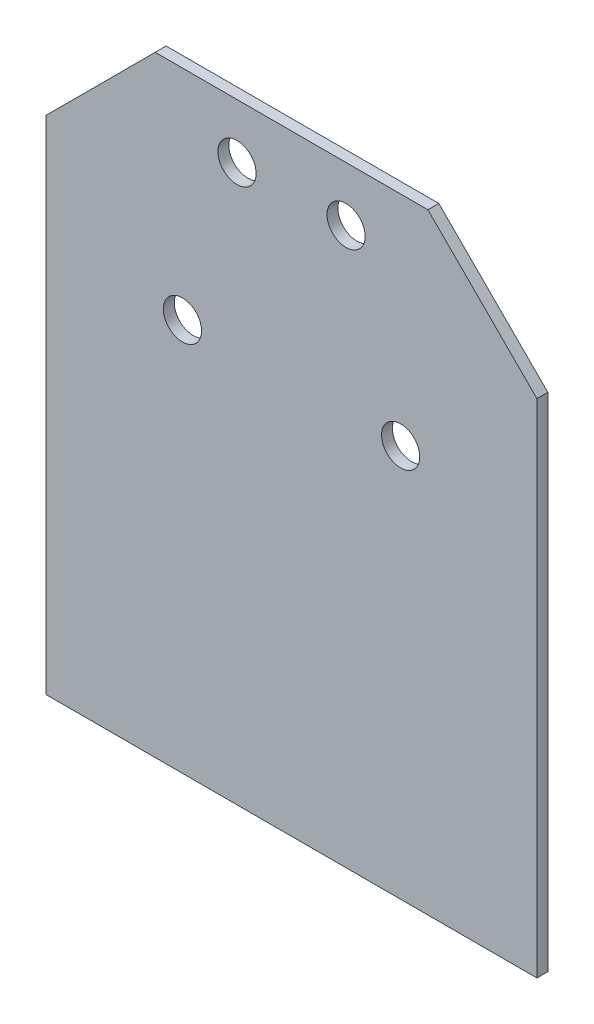
SolidWorks part; units mm, degrees
ref_plane "Piano frontale" through (0, 0, 0) normal (0, 0, 1) x (1, 0, 0)
ref_plane "Piano superiore" through (0, 0, 0) normal (0, 1, 0) x (1, 0, 0)
ref_plane "Piano destro" through (0, 0, 0) normal (1, 0, 0) x (0, 0, -1)
sketch "Schizzo1" plane through (0, 0, 0) normal (0, 0, 1) x (1, 0, 0)
  line L0 (-10, -19.992) -> (-10, 18.5766) construction
  line L1 (-37.9641, 8.7086) -> (33.9286, 8.7086) construction
  line L2 (-37.9641, -6.2914) -> (37.9641, -6.2914) construction
  line L3 (10, -17.3382) -> (10, 18.5766) construction
  line L4 (-22.5, -42.2914) -> (22.5, -42.2914)
  line L5 (-22.5, -42.2914) -> (-22.5, 3.7086)
  line L6 (-12.5, 13.7086) -> (12.5, 13.7086)
  line L7 (22.5, -42.2914) -> (22.5, 3.7086)
  line L8 (-22.5, -42.2914) -> (22.5, 13.7086) construction
  line L9 (-22.5, 13.7086) -> (22.5, -42.2914) construction
  line L10 (0, -42.2914) -> (0, 13.7086) construction
  line L11 (12.5, 13.7086) -> (22.5, 3.7086)
  line L12 (-22.5, 3.7086) -> (-12.5, 13.7086)
  circle A0 centre (5, 8.7086) radius 1.75
  circle A1 centre (-5, 8.7086) radius 1.75
  circle A2 centre (10, -6.2914) radius 1.75
  circle A3 centre (-10, -6.2914) radius 1.75
  point P12 (0, -14.2914)
  dimension "D1" = 3.5
  dimension "D2" = 56
  dimension "D3" = 15
  dimension "D4" = 36
  dimension "D5" = 45
  dimension "D7" = 10
  dimension "D9" = 10
extrude "Estrusione-Estrusione1" add sketch "Schizzo1" along normal blind 1
